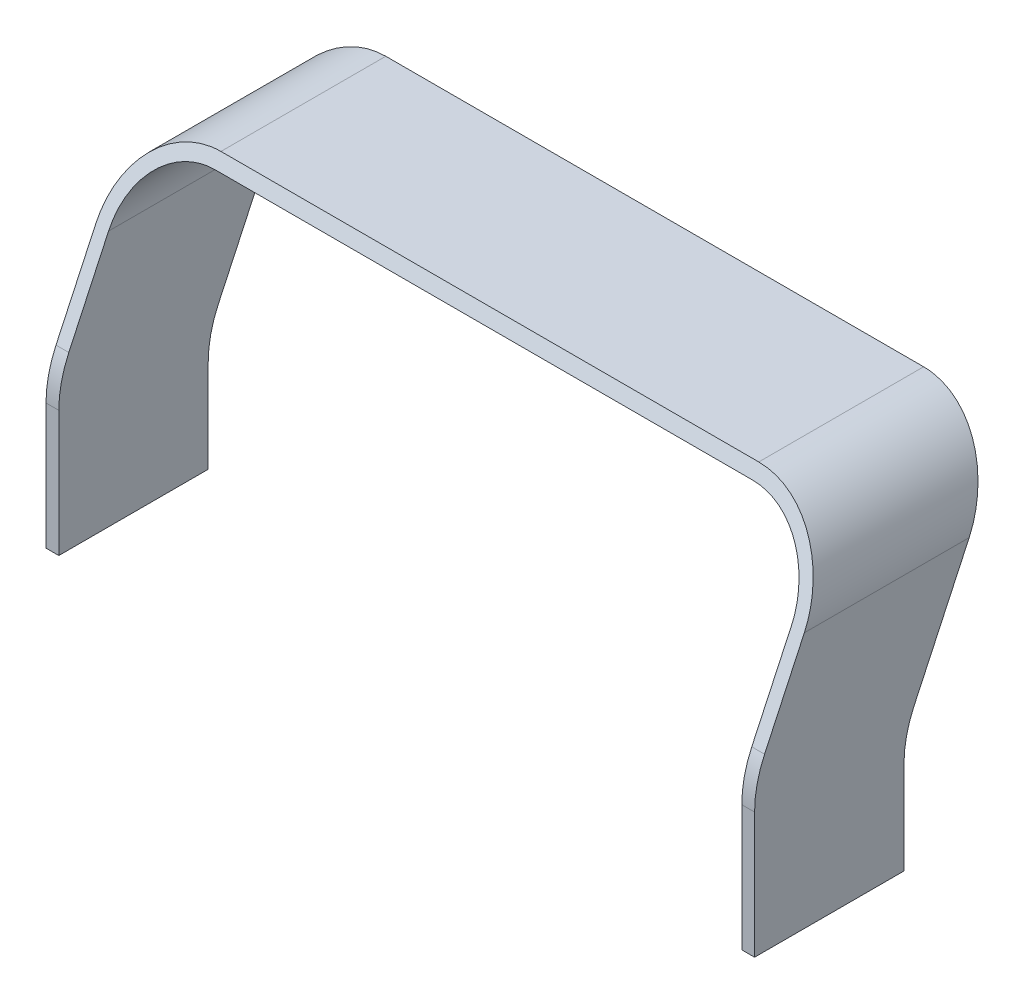
SolidWorks part; units mm, degrees
ref_plane "Front Plane" through (0, 0, 0) normal (0, 0, 1) x (1, 0, 0)
ref_plane "Top Plane" through (0, 0, 0) normal (0, 1, 0) x (1, 0, 0)
ref_plane "Right Plane" through (0, 0, 0) normal (1, 0, 0) x (0, 0, -1)
sketch "Sketch1" plane through (0, 0, 0) normal (0, 0, 1) x (1, 0, 0)
  line L0 (-83, 5) -> (-83, 65)
  line L1 (-63, 85) -> (63, 85)
  line L2 (83, 65) -> (83, 5)
  line L3 (-80, 5) -> (-80, 65)
  line L4 (-63, 82) -> (63, 82)
  line L5 (80, 65) -> (80, 5)
  line L6 (-83, 5) -> (-80, 5)
  line L7 (80, 5) -> (83, 5)
  arc A0 (63, 85) -> (83, 65) centre (63, 65) cw
  arc A1 (-83, 65) -> (-63, 85) centre (-63, 65) cw
  arc A2 (-80, 65) -> (-63, 82) centre (-63, 65) cw
  arc A3 (63, 82) -> (80, 65) centre (63, 65) cw
  dimension "D2" = 20
  dimension "D1" = 80
  dimension "D3" = 3
extrude "Boss-Extrude1" add sketch "Sketch1" along normal blind 70
sketch "Sketch2" plane through (-83, 0, 0) normal (-1, 0, 0) x (0, 0, 1)
  line L0 (49.0162, 85) -> (70, 40)
  line L1 (70, 85) -> (0, 85) construction
  line L2 (70, 65) -> (70, 5) construction
  line L3 (10.3979, 85) -> (35, 32.2407)
  line L4 (35, 32.2407) -> (35, 4.8709)
  line L5 (35, 4.8709) -> (0, 4.8709)
  line L6 (0, 0) -> (0, 30) construction
  line L7 (0, 4.8709) -> (0, 85)
  line L8 (0, 85) -> (10.3979, 85)
  line L9 (49.0162, 85) -> (70, 85)
  line L10 (70, 85) -> (70, 40)
  dimension "D1" = 25
  dimension "D2" = 45
  dimension "D3" = 35
  dimension "D4" = 35
extrude "Cut-Extrude1" cut sketch "Sketch2" against normal through all
fillet "Fillet1" radius 25 4 edges at (81.5, 32.2407, 35) (-81.5, 32.2407, 35) (81.5, 40, 70) (-81.5, 40, 70)
sketch "Sketch3" plane through (0, 0, 0) normal (1, 0, 0) x (0, 0, -1)
  line L0 (-49.0162, 85) -> (-10.3979, 85) construction
  line L1 (-31.207, 85) -> (-28.207, 85)
  line L2 (-31.207, 85) -> (-31.207, 77)
  line L3 (-31.207, 77) -> (-28.207, 77)
  line L4 (-28.207, 85) -> (-28.207, 77)
  line L5 (-29.707, 85) -> (-29.707, 67.4423) construction
  dimension "D1" = 1.5
  dimension "D2" = 3
  dimension "D3" = 8
extrude "Boss-Extrude2" add sketch "Sketch3" along normal up to surface (83 mm away) and the other way up to surface other way up to face at (-75.0711, 77.0711, 33.4044)
fillet "Fillet2" radius 10 2 edges at (75.0416, 77, 29.707) (-75.0416, 77, 29.707)
